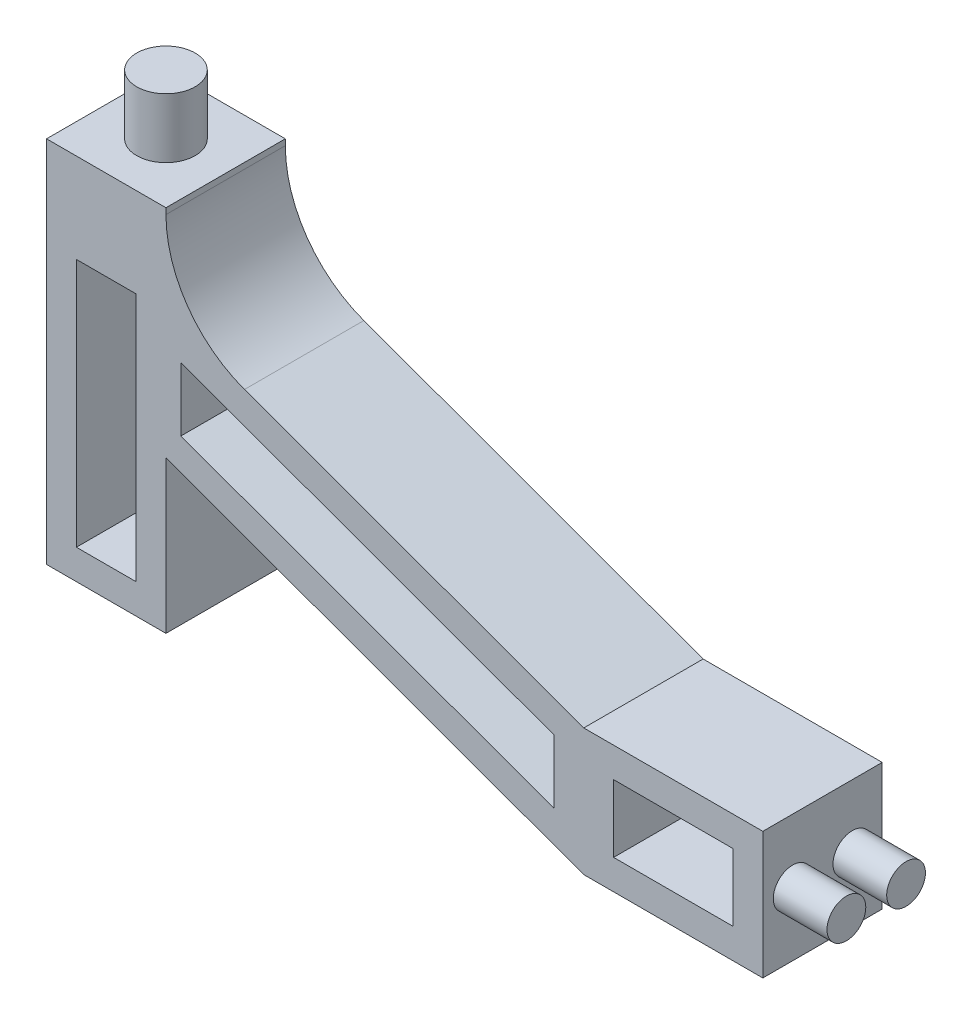
SolidWorks part; units mm, degrees
ref_plane "Plan de face" through (0, 0, 0) normal (0, 0, 1) x (1, 0, 0)
ref_plane "Plan de dessus" through (0, 0, 0) normal (0, 1, 0) x (1, 0, 0)
ref_plane "Plan de droite" through (0, 0, 0) normal (1, 0, 0) x (0, 0, -1)
sketch "Esquisse1" plane through (0, 0, 0) normal (0, 0, 1) x (1, 0, 0)
  line L0 (0, 0) -> (0, 21.2836)
  line L2 (-110, 46.7615) -> (-110, 61.7615)
  line L3 (-110, 61.7615) -> (-130, 61.7615)
  line L6 (0, 0) -> (-40, 0)
  line L7 (-40, 0) -> (-110, 25.4779)
  line L8 (-110, 25.4779) -> (-110, 0)
  line L9 (-110, 0) -> (-130, 0)
  line L10 (-130, 0) -> (-130, 61.7615)
  line L11 (-107.5, 40.5307) -> (-45, 17.7825)
  line L16 (-110, 46.7615) -> (-40, 21.2836)
  line L17 (-40, 21.2836) -> (0, 21.2836)
  line L21 (-45, 7.1407) -> (-107.5, 29.8889)
  line L23 (-115, 5) -> (-125, 5)
  line L24 (-125, 5) -> (-125, 46.7615)
  line L27 (-40, 0) -> (-40, 21.2836) construction
  line L28 (-110, 46.7615) -> (-130, 46.7615) construction
  line L29 (-125, 46.7615) -> (-115, 46.7615)
  line L30 (-45, 7.1407) -> (-45, 17.7825)
  line L32 (-107.5, 29.8889) -> (-107.5, 40.5307)
  line L33 (-115, 46.7615) -> (-115, 5)
  line L34 (-110, 25.4779) -> (-110, 46.7615) construction
  line L35 (-15, 10.6418) -> (0, 10.6418) construction
  line L36 (-35, 16.2836) -> (-15, 16.2836)
  line L37 (-35, 16.2836) -> (-35, 5)
  line L38 (-35, 5) -> (-15, 5)
  line L39 (-15, 16.2836) -> (-15, 5)
  point P8 (-120, 61.7615)
  point P21 (-110.89, 59.025)
  point P22 (-100.89, 59.025)
  dimension "D1" = 120
  dimension "D2" = 20
  dimension "D3" = 20
  dimension "D4" = 15
  dimension "D5" = 20
  dimension "D6" = 5
  dimension "D7" = 5
  dimension "D8" = 5
  dimension "D9" = 40
  dimension "D10" = 5
  dimension "D11" = 5
  dimension "D12" = 5
  dimension "D13" = 5
  dimension "D14" = 5
  dimension "D15" = 15
  dimension "D16" = 5
  dimension "D17" = 5
extrude "Boss.-Extru.1" add sketch "Esquisse1" along normal blind 20
fillet "Congé1" radius 20 1 edges at (-110, 46.7615, 10)
sketch "Esquisse2" plane through (0, 61.7615, 0) normal (0, 1, 0) x (1, 0, 0)
  line L0 (-130, 0) -> (-110, -20) construction
  circle A0 centre (-120, -10) radius 4.9
  dimension "D1" = 4.9
extrude "Boss.-Extru.2" add sketch "Esquisse2" along normal blind 10
sketch "Esquisse4" plane through (0, 0, 0) normal (1, 0, 0) x (0, 0, -1)
  line L1 (-47.107, 29.8612) -> (15.7339, 29.8612)
  line L2 (-47.107, 29.8612) -> (-47.107, -5.2218)
  line L3 (-47.107, -5.2218) -> (15.7339, -5.2218)
  line L4 (15.7339, 29.8612) -> (15.7339, -5.2218)
extrude "Enlèv. mat.-Extru.1" cut sketch "Esquisse4" against normal blind 10
sketch "Esquisse5" [suppressed] plane through (0, 0, 20) normal (0, 0, 1) x (1, 0, 0)
  line L0 (-10, 11.0932) -> (0, 11.0932) construction
  line L3 (0, 0) -> (0, 11.0932) construction
  circle A0 centre (-5, 11.0932) radius 3.5
  circle A1 centre (5, 11.0932) radius 3.5
  dimension "D1" = 7
  dimension "D2" = 10
extrude "Enlèv. mat.-Extru.2" [suppressed] cut sketch "Esquisse5" against normal through all
sketch "Esquisse6" plane through (-10, 0, 0) normal (1, 0, 0) x (0, 0, -1)
  line L0 (-20, 10.6418) -> (-10, 10.6418) construction
  line L1 (-20, 0) -> (-20, 21.2836) construction
  line L3 (-10, 0) -> (-10, 10.6418) construction
  line L4 (-20, 0) -> (0, 0) construction
  circle A0 centre (-15, 10.6418) radius 3.25
  circle A1 centre (-5, 10.6418) radius 3.25
  dimension "D1" = 6.5
extrude "Boss.-Extru.3" add sketch "Esquisse6" along normal blind 9
equation "\"L\"=20"
